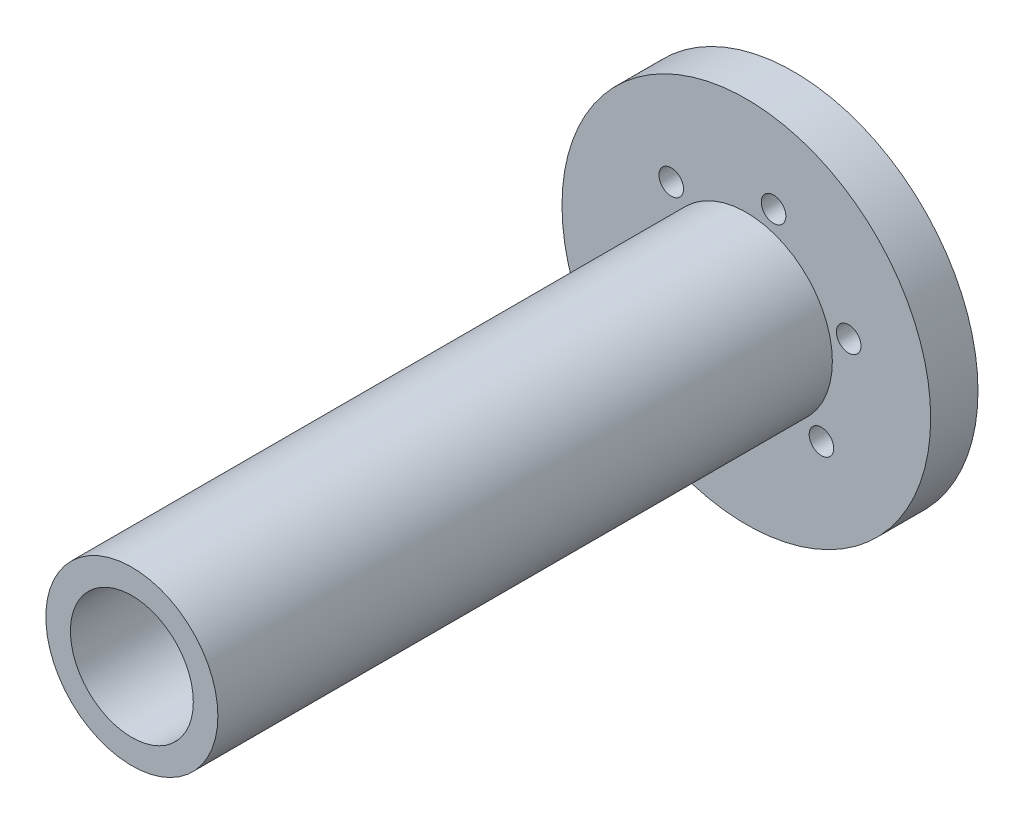
SolidWorks part; units mm, degrees
ref_plane "前视基准面" through (0, 0, 0) normal (0, 0, 1) x (1, 0, 0)
ref_plane "上视基准面" through (0, 0, 0) normal (0, 1, 0) x (1, 0, 0)
ref_plane "右视基准面" through (0, 0, 0) normal (1, 0, 0) x (0, 0, -1)
sketch "草图1" plane through (0, 0, 0) normal (0, 0, 1) x (1, 0, 0)
  circle A0 centre (0, 0) radius 50
extrude "凸台-拉伸1" add sketch "草图1" along normal blind 7.7
sketch "草图2" plane through (0, 0, 7.7) normal (0, 0, 1) x (1, 0, 0)
  circle A0 centre (4.429, 16.6717) radius 2
  circle A1 centre (16.6526, 4.5002) radius 2
  circle A2 centre (12.2236, -12.1715) radius 2
  circle A3 centre (-4.429, -16.6717) radius 2
  circle A4 centre (-16.6526, -4.5002) radius 2
  circle A5 centre (-12.2236, 12.1715) radius 2
  point P16 (0, 0)
  dimension "D1" = 17.25
  dimension "D2" = 6
extrude "切除-拉伸1" cut sketch "草图2" against normal blind 7.7
sketch "草图3" plane through (0, 0, 7.7) normal (0, 0, 1) x (1, 0, 0)
  circle A0 centre (0, 0) radius 10
extrude "拉伸-薄壁1" add sketch "草图3" along normal blind 100 thin
sketch "草图4" plane through (0, 0, 7.7) normal (0, 0, 1) x (1, 0, 0)
  circle A0 centre (0, 0) radius 30
extrude "切除-拉伸-薄壁1" cut sketch "草图4" against normal blind 10 thin
